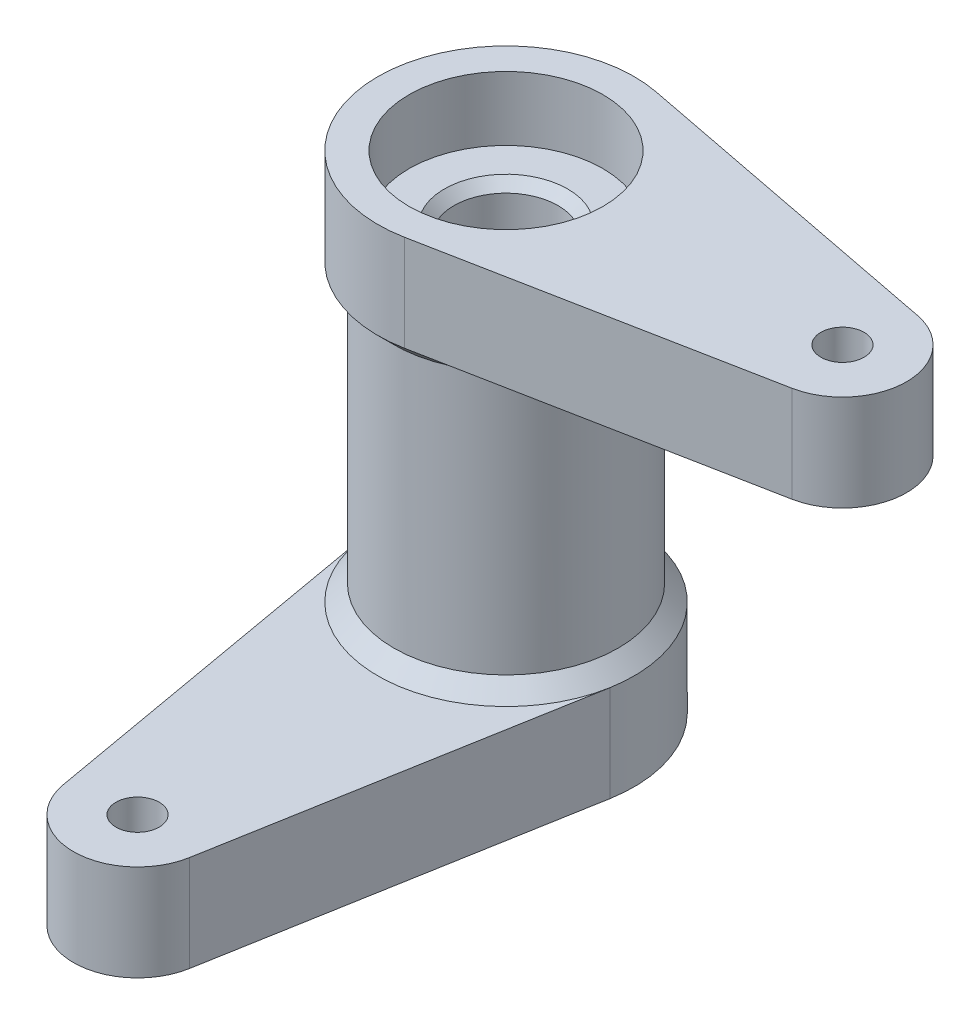
SolidWorks part; units mm, degrees
material "PET"
ref_plane "Plan de face" through (0, 0, 0) normal (0, 0, 1) x (1, 0, 0)
ref_plane "Plan de dessus" through (0, 0, 0) normal (0, 1, 0) x (1, 0, 0)
ref_plane "Plan de droite" through (0, 0, 0) normal (1, 0, 0) x (0, 0, -1)
sketch "Esquisse1" plane through (0, 0, 0) normal (0, 0, 1) x (1, 0, 0)
  line L0 (0, 0) -> (0, 30.4) construction
  line L1 (-6.05, 0) -> (-6.05, 4)
  line L2 (-6.05, 4) -> (-3.85, 4)
  line L3 (-3.25, 4.6) -> (-3.25, 25.8)
  line L4 (-3.85, 26.4) -> (-6.05, 26.4)
  line L5 (-6.05, 26.4) -> (-6.05, 30.4)
  line L6 (-6.05, 30.4) -> (-8, 30.4)
  line L7 (-8, 30.4) -> (-8, 24.4)
  line L8 (-8, 24.4) -> (-7, 23.4)
  line L9 (-7, 23.4) -> (-7, 7)
  line L10 (-7, 7) -> (-8, 6)
  line L11 (-8, 6) -> (-8, 0)
  line L12 (-8, 0) -> (-6.05, 0)
  line L13 (-3.25, 25.8) -> (-3.85, 26.4)
  line L14 (-3.85, 4) -> (-3.25, 4.6)
  point P6 (-3.25, 4)
  point P7 (-3.25, 26.4)
  point P19 (0, 30.4)
  point P20 (0, 0)
  point P21 (-7.025, 0)
  dimension "D1" = 16
  dimension "D2" = 6.5
  dimension "D3" = 12.1
  dimension "D4" = 30.4
  dimension "D5" = 6
  dimension "D6" = 4
  dimension "D7" = 14
revolve "Révolution1" add sketch "Esquisse1" angle 360 about L0
sketch "Esquisse2" plane through (0, 0, 0) normal (0, 1, 0) x (1, 0, 0)
  line L0 (-7.8781, -1.3913) -> (-3.939, -23.6957)
  line L2 (3.939, -23.6957) -> (7.8781, -1.3913)
  circle A0 centre (0, -23) radius 1.35
  arc A1 (3.939, -23.6957) -> (-3.939, -23.6957) centre (0, -23) cw
  arc A6 (-7.8781, -1.3913) -> (7.8781, -1.3913) centre (0, 0) ccw
  circle A7 centre (0, 0) radius 8 construction
  dimension "D1" = 4
  dimension "D2" = 23
  dimension "D3" = 2.7
extrude "Boss.-Extru.2" add sketch "Esquisse2" along normal up to vertex (6 mm away) up to point (-8, 6, 0)
sketch "Esquisse3" plane through (0, 30.4, 0) normal (0, 1, 0) x (1, 0, 0)
  line L0 (21.7619, 3.9268) -> (1.5238, 7.8535)
  line L1 (21.7619, -3.9268) -> (1.5238, -7.8535)
  line L2 (0, 0) -> (0, 8) construction
  line L3 (0, 0) -> (21, 0) construction
  circle A0 centre (21, 0) radius 1.35
  circle A1 centre (0, -23) radius 1.35 construction
  arc A2 (21.7619, -3.9268) -> (21.7619, 3.9268) centre (21, 0) ccw
  arc A3 (-3.939, -23.6957) -> (3.939, -23.6957) centre (0, -23) ccw construction
  arc A4 (1.5238, -7.8535) -> (1.5238, 7.8535) centre (0, 0) ccw
  circle A5 centre (0, 0) radius 8 construction
  dimension "D1" = 21
  dimension "D2" = 90
extrude "Boss.-Extru.3" add sketch "Esquisse3" against normal up to vertex (6 mm away) up to point (-8, 24.4, 0)
sketch "Esquisse4" plane through (0, 24.4, 0) normal (0, -1, 0) x (1, 0, 0)
  line L1 (21, -3.1754) -> (23.75, -1.5877)
  line L2 (23.75, -1.5877) -> (23.75, 1.5877)
  line L3 (23.75, 1.5877) -> (21, 3.1754)
  line L4 (21, 3.1754) -> (18.25, 1.5877)
  line L5 (18.25, 1.5877) -> (18.25, -1.5877)
  line L6 (18.25, -1.5877) -> (21, -3.1754)
  circle A0 centre (21, 0) radius 2.75 construction
  dimension "D1" = 5.5
extrude "Enlèv. mat.-Extru.1" cut sketch "Esquisse4" against normal blind 3
